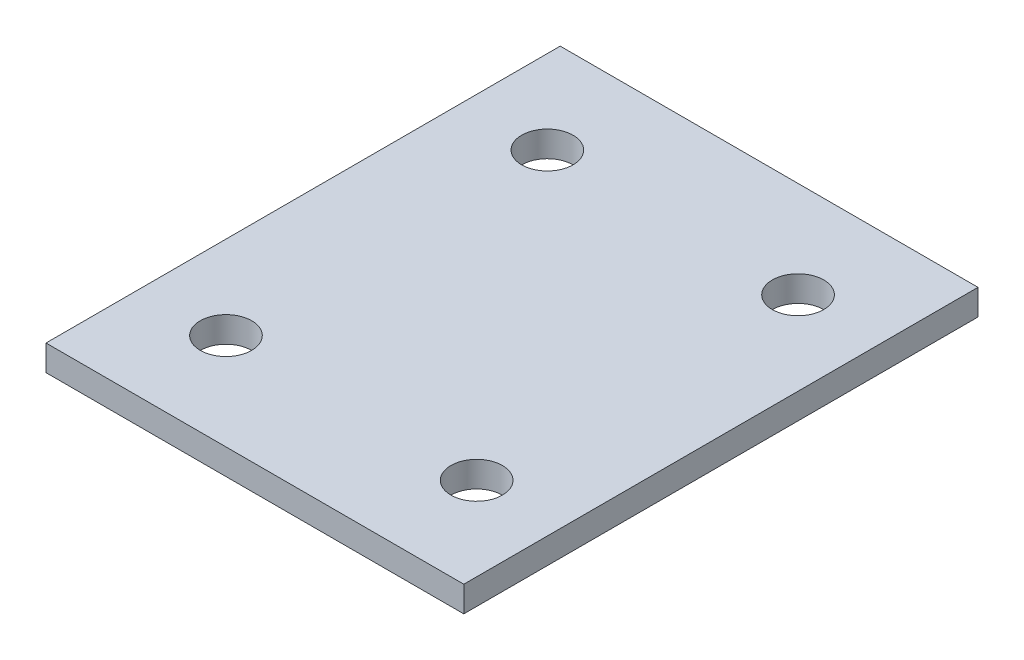
SolidWorks part; units mm, degrees
ref_plane "Front Plane" through (0, 0, 0) normal (0, 0, 1) x (1, 0, 0)
ref_plane "Top Plane" through (0, 0, 0) normal (0, 1, 0) x (1, 0, 0)
ref_plane "Right Plane" through (0, 0, 0) normal (1, 0, 0) x (0, 0, -1)
sketch "Sketch1" plane through (0, 0, 0) normal (0, 1, 0) x (1, 0, 0)
  line L0 (32.5, 80) -> (32.5, 0) construction
  line L1 (0, 0) -> (65, 0)
  line L2 (0, 0) -> (0, 80)
  line L3 (0, 80) -> (65, 80)
  line L4 (65, 0) -> (65, 80)
  line L5 (0, 40) -> (85.6544, 40) construction
  circle A0 centre (13, 65) radius 4
  circle A1 centre (13, 15) radius 4
  circle A2 centre (52, 15) radius 4
  circle A3 centre (52, 65) radius 4
  point P19 (0, 0)
  point P22 (65, 0)
  point P27 (0, 80)
  dimension "D3" = 8
  dimension "D1" = 65
  dimension "D2" = 80
  dimension "D4" = 39
  dimension "D5" = 50
extrude "Boss-Extrude1" add sketch "Sketch1" along normal blind 4
